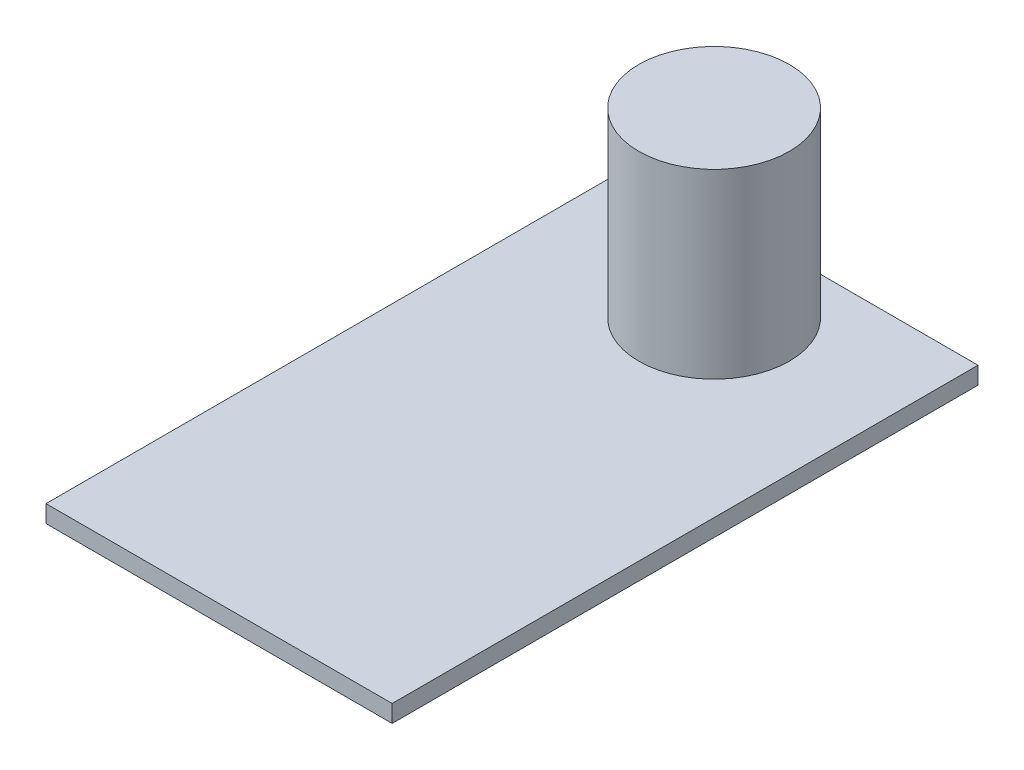
SolidWorks part; units mm, degrees
ref_plane "Front Plane" through (0, 0, 0) normal (0, 0, 1) x (1, 0, 0)
ref_plane "Top Plane" through (0, 0, 0) normal (0, 1, 0) x (1, 0, 0)
ref_plane "Right Plane" through (0, 0, 0) normal (1, 0, 0) x (0, 0, -1)
sketch "Sketch1" plane through (0, 0, 0) normal (0, 1, 0) x (1, 0, 0)
  line L1 (-40, 67.7) -> (0, 67.7)
  line L2 (-40, 67.7) -> (-40, 0)
  line L3 (-40, 0) -> (0, 0)
  line L4 (0, 67.7) -> (0, 0)
  dimension "D1" = 40
  dimension "D2" = 67.7
extrude "Boss-Extrude1" add sketch "Sketch1" along normal blind 2
sketch "Sketch2" plane through (0, 2, 0) normal (0, 1, 0) x (1, 0, 0)
  line L0 (0, 67.7) -> (-40, 67.7) construction
  line L1 (0, 0) -> (0, 67.7) construction
  circle A0 centre (-20, 57.2) radius 8.7
  dimension "D1" = 17.4
  dimension "D2" = 10.5
  dimension "D3" = 20
extrude "Boss-Extrude2" add sketch "Sketch2" along normal blind 21
